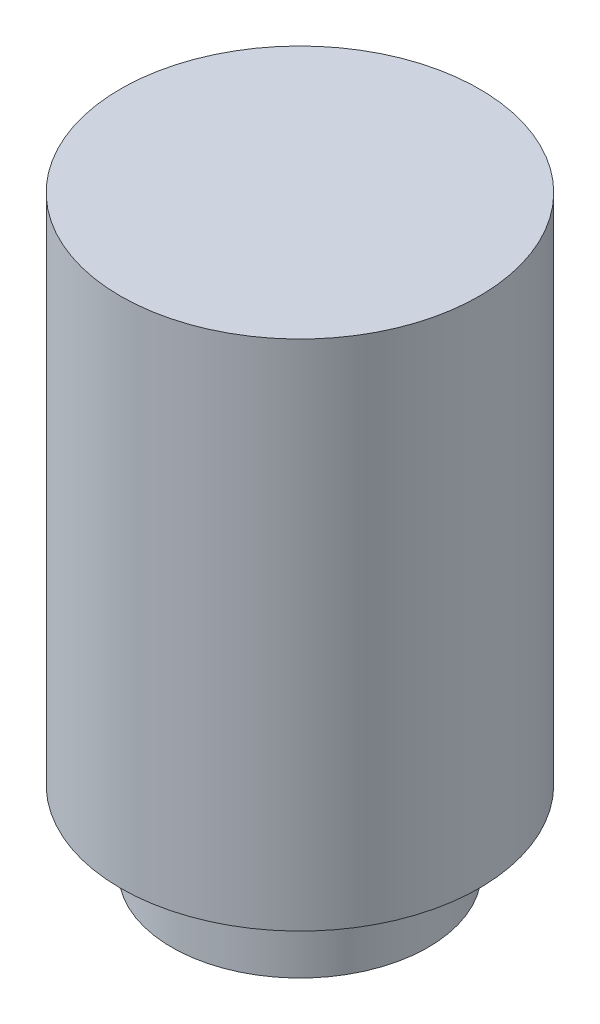
SolidWorks part; units mm, degrees
ref_plane "Front Plane" through (0, 0, 0) normal (0, 0, 1) x (1, 0, 0)
ref_plane "Top Plane" through (0, 0, 0) normal (0, 1, 0) x (1, 0, 0)
ref_plane "Right Plane" through (0, 0, 0) normal (1, 0, 0) x (0, 0, -1)
sketch "Sketch2" plane through (0, 0, 0) normal (0, 1, 0) x (1, 0, 0)
  circle A0 centre (0, 0) radius 70
extrude "Boss-Extrude1" add sketch "Sketch2" along normal blind 200
sketch "Sketch3" plane through (0, 0, 0) normal (0, -1, 0) x (1, 0, 0)
  circle A0 centre (0, 0) radius 50
extrude "Boss-Extrude2" add sketch "Sketch3" along normal blind 30
sketch "Sketch4" plane through (0, -30, 0) normal (0, -1, 0) x (1, 0, 0)
  circle A0 centre (0, 0) radius 30
extrude "Boss-Extrude3" add sketch "Sketch4" along normal blind 10
